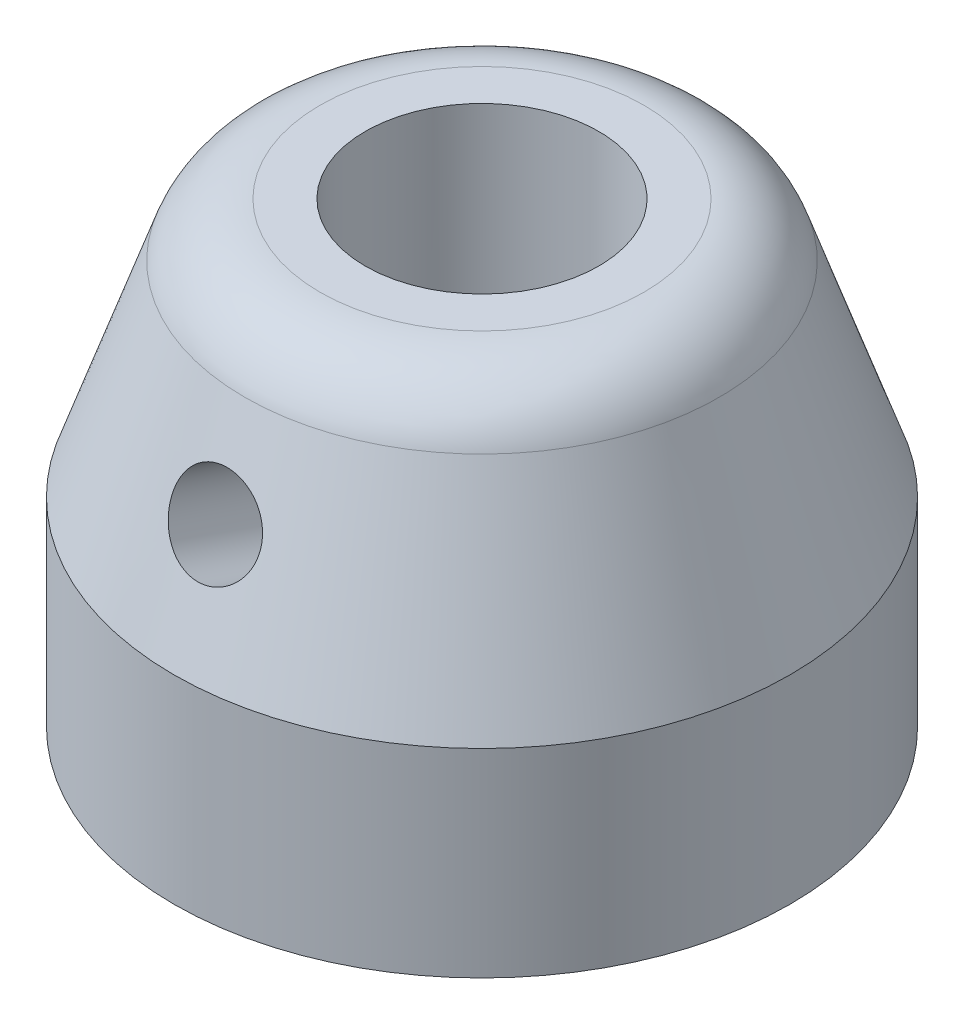
SolidWorks part; units mm, degrees
ref_plane "Front Plane" through (0, 0, 0) normal (0, 0, 1) x (1, 0, 0)
ref_plane "Top Plane" through (0, 0, 0) normal (0, 1, 0) x (1, 0, 0)
ref_plane "Right Plane" through (0, 0, 0) normal (1, 0, 0) x (0, 0, -1)
sketch "Sketch1" plane through (0, 0, 0) normal (0, 0, 1) x (1, 0, 0)
  line L0 (0, 0) -> (0, 46)
  line L1 (0, 0) -> (31, 0)
  line L2 (31, 0) -> (31, 20)
  line L3 (31, 20) -> (22, 46)
  line L4 (22, 46) -> (0, 46)
  dimension "D1" = 46
  dimension "D2" = 31
  dimension "D3" = 20
  dimension "D4" = 22
revolve "Revolve1" add sketch "Sketch1" angle 360 about L0
hole_wizard "M25x1.5 Tapped Hole1" positions "Sketch4" profile "Sketch5" tap size "M25x1.5" standard "DIN" end condition through all
sketch "Sketch4" plane through (0, 46, 0) normal (0, 1, 0) x (1, 0, 0)
  point P0 (0, 0)
  point P3 (0, 0)
sketch "Sketch5" plane through (0, 46, 0) normal (1, 0, 0) x (0, 0, 1)
  line L0 (0, 0) -> (0, 46)
  line L1 (0, 46) -> (11.75, 46)
  line L2 (11.75, 46) -> (11.75, 0)
  line L5 (11.75, 0) -> (0, 0)
  line L11 (0, -6.35) -> (0, 107.95) construction
  dimension "Thru Tap Drill Dia." = 23.5
  dimension "Thru Tap Drill Depth" = 46
cosmetic thread "Hole Thread3" parameters "D2"=25
cosmetic thread "Hole Thread4" parameters "D2"=25
fillet "Fillet2" radius 8 1 edges at (0, 46, -22)
sketch "Sketch11" plane through (0, 0, 0) normal (1, 0, 0) x (0, 0, -1)
  line L0 (-23.8634, 40.6169) -> (-31, 20) construction
  line L1 (-23.8634, 40.6169) -> (-31, 20) construction
ref_plane "Plane2" through (0, 11.7226, 33.8653) normal (0, 0.3271, 0.945) x (1, 0, 0)
hole_wizard "M10x1.0 Tapped Hole1" positions "Sketch12" profile "Sketch13" tap size "M10x1.0" standard "DIN"
sketch "Sketch12" plane through (0, 11.7226, 33.8653) normal (0, 0.3271, 0.945) x (1, 0, 0)
  line L0 (0, 30.5764) -> (0, 8.7593) construction
  point P0 (0, 20.5764)
  dimension "D1" = 10
sketch "Sketch13" plane through (0, 31.167, 27.1345) normal (1, 0, 0) x (0, -0.945, 0.3271)
  line L0 (0, 0) -> (0, 12.7039)
  line L1 (0, 12.7039) -> (4.5, 10)
  line L2 (4.5, 10) -> (4.5, 0)
  line L5 (4.5, 0) -> (0, 0)
  line L10 (0, 12.7039) -> (-4.5, 10) construction
  line L11 (0, -6.35) -> (0, 107.95) construction
  dimension "Tap Drill Dia." = 9
  dimension "Tap Drill Depth" = 10
  dimension "Drill Angle" = 118
cosmetic thread "Hole Thread5" parameters "D1"=20, "D2"=10
sketch "Sketch14" plane through (0, 0, 0) normal (1, 0, 0) x (0, 0, -1)
  line L0 (-18.2034, 0) -> (0, 0)
  line L1 (-31, 0) -> (31, 0) construction
  line L2 (0, 0) -> (0, 2)
  line L3 (0, 2) -> (-12.5, 2)
  arc A0 (-12.5, 2) -> (-18.2034, 0) centre (0, -42.778) ccw
  point P7 (0, 0)
  point P8 (0, 0)
  point P9 (0, 0)
  dimension "D1" = 12.5
  dimension "D3" = 46.49
  dimension "D2" = 2
revolve "Cut-Revolve1" cut sketch "Sketch14" angle 360 about L2
